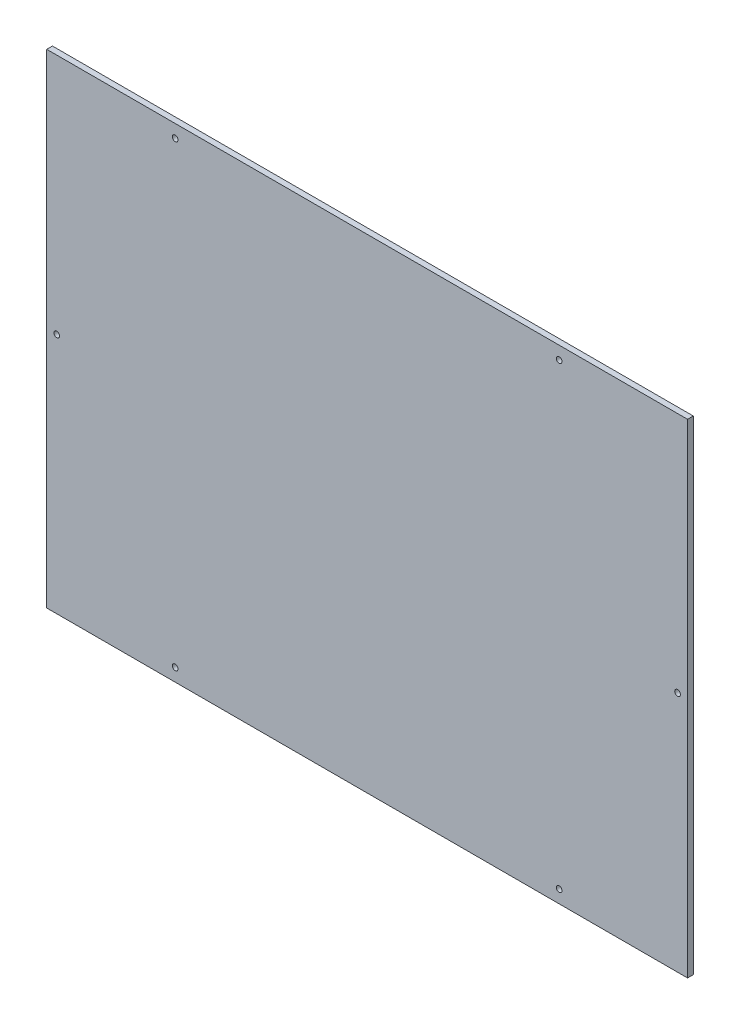
SolidWorks part; units mm, degrees
ref_plane "Piano frontale" through (0, 0, 0) normal (0, 0, 1) x (1, 0, 0)
ref_plane "Piano superiore" through (0, 0, 0) normal (0, 1, 0) x (1, 0, 0)
ref_plane "Piano destro" through (0, 0, 0) normal (1, 0, 0) x (0, 0, -1)
sketch "Schizzo1" plane through (0, 0, 0) normal (0, 0, 1) x (1, 0, 0)
  line L0 (-224.5, 351.6275) -> (-224.5, -66.2585) construction
  line L1 (0, 0) -> (-449, 0)
  line L2 (0, 0) -> (0, 339)
  line L3 (0, 339) -> (-449, 339)
  line L4 (-449, 0) -> (-449, 339)
  line L5 (-387.9788, 169.5) -> (120.8821, 169.5) construction
  circle A0 centre (-90, 330) radius 2
  circle A1 centre (-7, 169.5) radius 2
  circle A2 centre (-359, 330) radius 2
  circle A3 centre (-442, 169.5) radius 2
  circle A4 centre (-359, 9) radius 2
  circle A7 centre (-90, 9) radius 2
  point P9 (-224.5, 169.5)
  dimension "D3" = 4
  dimension "D1" = 449
  dimension "314" = 339
  dimension "D4" = 9
  dimension "D5" = 90
  dimension "D6" = 7
extrude "Estrusione-Estrusione1" add sketch "Schizzo1" along normal blind 4
